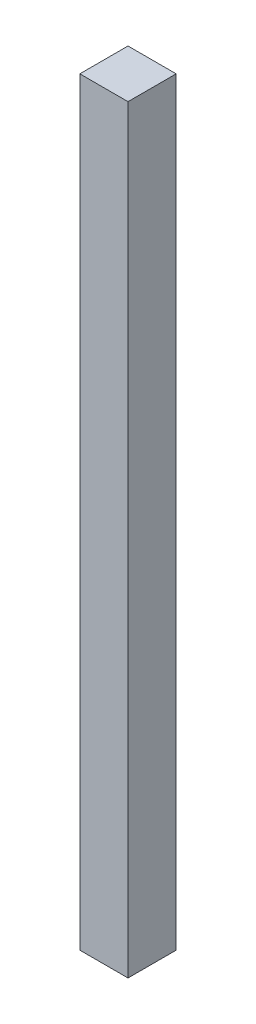
SolidWorks part; units mm, degrees
ref_plane "Front Plane" through (0, 0, 0) normal (0, 0, 1) x (1, 0, 0)
ref_plane "Top Plane" through (0, 0, 0) normal (0, 1, 0) x (1, 0, 0)
ref_plane "Right Plane" through (0, 0, 0) normal (1, 0, 0) x (0, 0, -1)
sketch "Sketch2" plane through (0, 0, 0) normal (0, 1, 0) x (1, 0, 0)
  line L1 (2, 2) -> (-2, 2)
  line L2 (2, 2) -> (2, -2)
  line L3 (2, -2) -> (-2, -2)
  line L4 (-2, 2) -> (-2, -2)
  line L5 (2, 2) -> (-2, -2) construction
  line L6 (2, -2) -> (-2, 2) construction
  point P0 (0, 0)
  dimension "D1" = 4
  dimension "D2" = 4
extrude "Boss-Extrude1" add sketch "Sketch2" along normal blind 63
